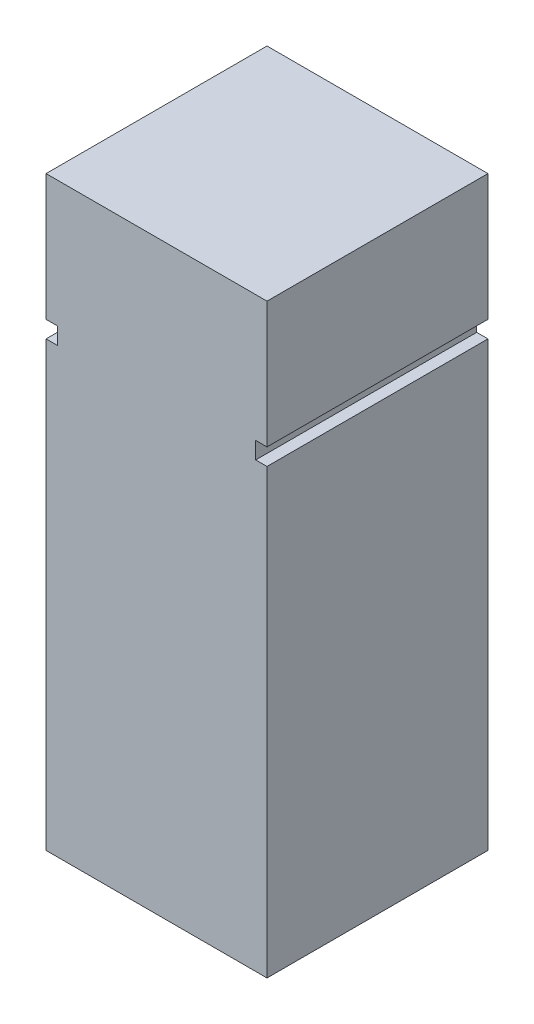
SolidWorks part; units mm, degrees
ref_plane "Front" through (0, 0, 0) normal (0, 0, 1) x (1, 0, 0)
ref_plane "Top" through (0, 0, 0) normal (0, 1, 0) x (1, 0, 0)
ref_plane "Right" through (0, 0, 0) normal (1, 0, 0) x (0, 0, -1)
sketch "Sketch1" plane through (0, 0, 0) normal (0, 0, 1) x (1, 0, 0)
  line L1 (-31.7522, 22.9478) -> (-6.8602, 22.9478)
  line L2 (-31.7522, 22.9478) -> (-31.7522, -43.0922)
  line L3 (-31.7522, -43.0922) -> (-6.8602, -43.0922)
  line L4 (-6.8602, 22.9478) -> (-6.8602, -43.0922)
  dimension "D1" = 66.04
  dimension "D2" = 24.892
extrude "Boss-Extrude1" add sketch "Sketch1" along normal blind 24.892
sketch "Sketch2" plane through (0, 0, 24.892) normal (0, 0, 1) x (1, 0, 0)
  line L1 (-31.7522, 22.9478) -> (-6.8602, 22.9478)
  line L2 (-31.7522, 22.9478) -> (-31.7522, 8.7238)
  line L3 (-31.7522, 8.7238) -> (-6.8602, 8.7238)
  line L4 (-31.7522, 22.9478) -> (-31.7522, -43.0922)
  line L5 (-31.7522, -43.0922) -> (-6.8602, -43.0922)
  line L6 (-6.8602, -43.0922) -> (-6.8602, 22.9478)
  line L7 (-6.8602, 22.9478) -> (-31.7522, 22.9478)
  line L8 (-31.7522, 22.9478) -> (-31.7522, -43.0922)
  line L9 (-31.7522, -43.0922) -> (-6.8602, -43.0922)
  line L10 (-6.8602, -43.0922) -> (-6.8602, 22.9478)
  line L11 (-6.8602, 22.9478) -> (-31.7522, 22.9478)
  line L12 (-6.8602, 22.9478) -> (-6.8602, 8.7238)
  line L13 (-31.7522, 8.7238) -> (-6.8602, 8.7238)
  line L14 (-31.7522, 8.7238) -> (-31.7522, 6.8188)
  line L15 (-31.7522, 6.8188) -> (-6.8602, 6.8188)
  line L16 (-6.8602, 8.7238) -> (-6.8602, 6.8188)
  line L17 (-31.7522, 8.7238) -> (-30.4822, 8.7238)
  line L18 (-31.7522, 8.7238) -> (-31.7522, 6.8188)
  line L19 (-31.7522, 6.8188) -> (-30.4822, 6.8188)
  line L20 (-30.4822, 8.7238) -> (-30.4822, 6.8188)
  line L21 (-6.8602, 8.7238) -> (-8.1302, 8.7238)
  line L22 (-6.8602, 8.7238) -> (-6.8602, 6.8188)
  line L23 (-6.8602, 6.8188) -> (-8.1302, 6.8188)
  line L24 (-8.1302, 8.7238) -> (-8.1302, 6.8188)
  line M10 (-31.7522, 22.9478) -> (-31.7522, -43.0922)
  dimension "D2" = 14.224
  dimension "D3" = 1.905
  dimension "D4" = 1.27
  dimension "D5" = 1.27
  dimension "D1" = 0
extrude "Cut-Extrude1" cut sketch "Sketch2" against normal up to surface (24.892 mm away) contours L20 L3 L15 M10 | L3 L24 L15 L10 up to face at (-19.3062, -10.0722, 0)
